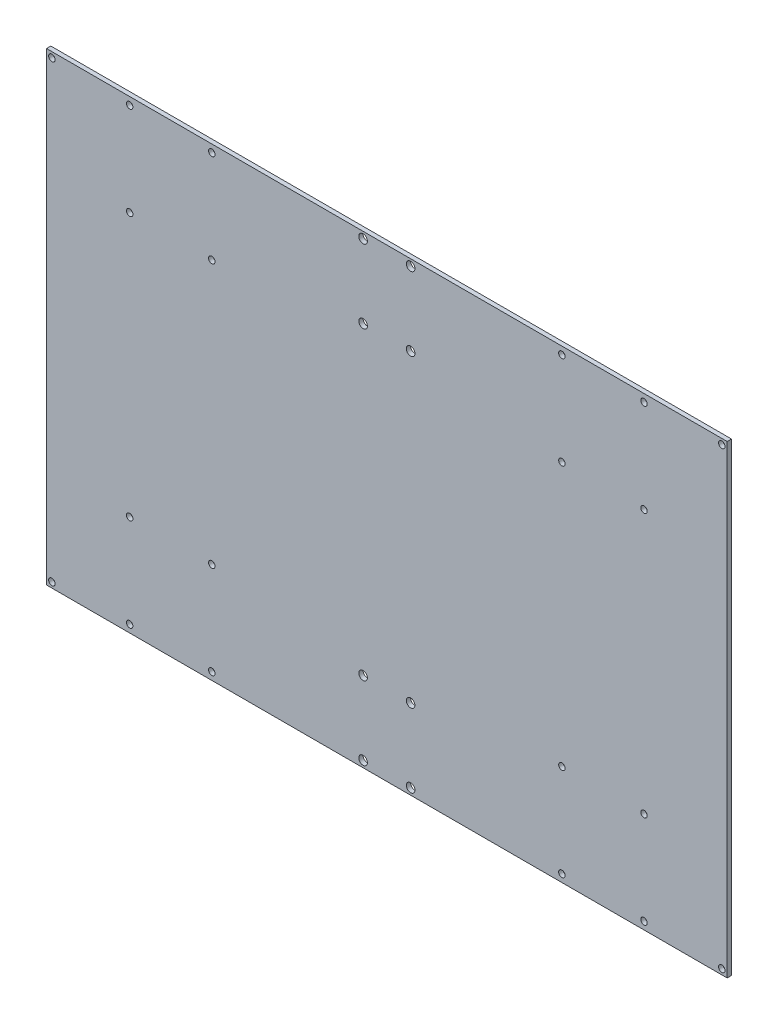
SolidWorks part; units mm, degrees
ref_plane "前视基准面" through (0, 0, 0) normal (0, 0, 1) x (1, 0, 0)
ref_plane "上视基准面" through (0, 0, 0) normal (0, 1, 0) x (1, 0, 0)
ref_plane "右视基准面" through (0, 0, 0) normal (1, 0, 0) x (0, 0, -1)
sketch "草图1" plane through (0, 0, 0) normal (0, 0, 1) x (1, 0, 0)
  line L1 (-157.5, -107.5) -> (157.5, -107.5)
  line L2 (-157.5, -107.5) -> (-157.5, 107.5)
  line L3 (-157.5, 107.5) -> (157.5, 107.5)
  line L4 (157.5, -107.5) -> (157.5, 107.5)
  line L5 (-157.5, -107.5) -> (157.5, 107.5) construction
  line L6 (-157.5, 107.5) -> (157.5, -107.5) construction
  point P0 (0, 0)
  dimension "D1" = 215
  dimension "D2" = 315
extrude "凸台-拉伸1" add sketch "草图1" along normal blind 2
sketch "草图2" plane through (0, 0, 2) normal (0, 0, 1) x (1, 0, 0)
  line L0 (-157.5, 107.5) -> (-157.5, -107.5) construction
  line L1 (157.5, 107.5) -> (-157.5, 107.5) construction
  line L2 (-157.5, 0) -> (157.5, 0) construction
  line L3 (157.5, -107.5) -> (157.5, 107.5) construction
  line L4 (0, 107.5) -> (0, -107.5) construction
  line L5 (-157.5, -107.5) -> (157.5, -107.5) construction
  circle A0 centre (-155, 105) radius 1.5
  circle A1 centre (155, 105) radius 1.5
  circle A2 centre (155, -105) radius 1.5
  circle A3 centre (-155, -105) radius 1.5
  dimension "D1" = 3
  dimension "D2" = 2.5
  dimension "D3" = 2.5
extrude "切除-拉伸1" cut sketch "草图2" against normal blind 2
sketch "草图3" plane through (0, 0, 2) normal (0, 0, 1) x (1, 0, 0)
  line L0 (0, 107.5) -> (0, -107.5) construction
  line L1 (157.5, 107.5) -> (-157.5, 107.5) construction
  line L2 (-157.5, -107.5) -> (157.5, -107.5) construction
sketch "草图4" plane through (0, 0, 2) normal (0, 0, 1) x (1, 0, 0)
  line L0 (-100, 107.5) -> (-100, -107.5) construction
  line L1 (157.5, 107.5) -> (-157.5, 107.5) construction
  line L2 (-157.5, -107.5) -> (157.5, -107.5) construction
  line L3 (100, 107.5) -> (100, -107.5) construction
  line L4 (0, 107.5) -> (0, -107.5) construction
  dimension "D1" = 100
  dimension "D2" = 100
sketch "草图5" plane through (0, 0, 2) normal (0, 0, 1) x (1, 0, 0)
  circle A0 centre (-119, 104) radius 1.5
  circle A1 centre (-81, 104) radius 1.5
  circle A2 centre (-119, 61) radius 1.5
  circle A3 centre (-81, 61) radius 1.5
  circle A4 centre (81, 104) radius 1.5
  circle A5 centre (119, 104) radius 1.5
  circle A6 centre (119, 61) radius 1.5
  circle A7 centre (81, 61) radius 1.5
  circle A8 centre (81, -61) radius 1.5
  circle A9 centre (119, -61) radius 1.5
  circle A10 centre (119, -104) radius 1.5
  circle A11 centre (81, -104) radius 1.5
  circle A12 centre (-119, -61) radius 1.5
  circle A13 centre (-81, -61) radius 1.5
  circle A14 centre (-81, -104) radius 1.5
  circle A15 centre (-119, -104) radius 1.5
extrude "切除-拉伸2" cut sketch "草图5" against normal blind 2
sketch "草图6" plane through (0, 0, 2) normal (0, 0, 1) x (1, 0, 0)
  circle A0 centre (-11, 104.5) radius 2
  circle A1 centre (11, 104.5) radius 2
  circle A2 centre (-11, 70.5) radius 2
  circle A3 centre (11, 70.5) radius 2
  circle A4 centre (-11, -70.5) radius 2
  circle A5 centre (11, -70.5) radius 2
  circle A6 centre (-11, -104.5) radius 2
  circle A7 centre (11, -104.5) radius 2
extrude "切除-拉伸3" cut sketch "草图6" against normal blind 2
